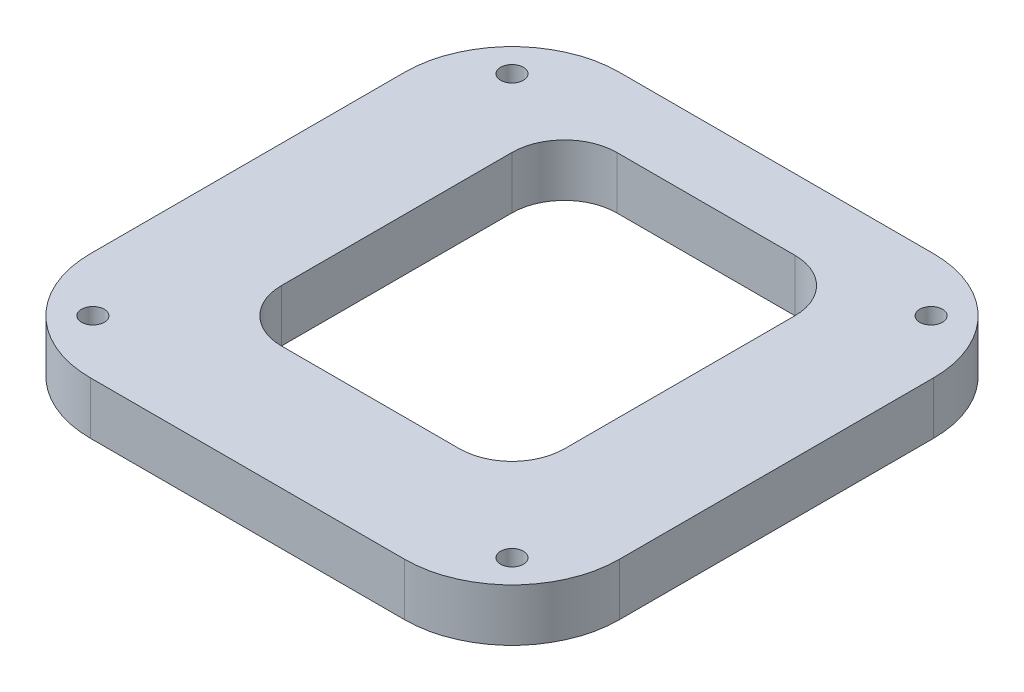
SolidWorks part; units mm, degrees
ref_plane "前视基准面" through (0, 0, 0) normal (0, 0, 1) x (1, 0, 0)
ref_plane "上视基准面" through (0, 0, 0) normal (0, 1, 0) x (1, 0, 0)
ref_plane "右视基准面" through (0, 0, 0) normal (1, 0, 0) x (0, 0, -1)
other "Configuration Table"
sketch "草图1" plane through (0, 0, 0) normal (0, 1, 0) x (1, 0, 0)
  line L0 (0, 62.6062) -> (0, -64.1627) construction
  line L1 (50.5, -50.5) -> (-50.5, -50.5)
  line L2 (50.5, -50.5) -> (50.5, 50.5)
  line L3 (50.5, 50.5) -> (-50.5, 50.5)
  line L4 (-50.5, -50.5) -> (-50.5, 50.5)
  line L5 (50.5, -50.5) -> (-50.5, 50.5) construction
  line L6 (50.5, 50.5) -> (-50.5, -50.5) construction
  line L8 (-27, 37) -> (27, 37)
  line L9 (-27, 37) -> (-27, -27)
  line L10 (-27, -27) -> (27, -27)
  line L11 (27, 37) -> (27, -27)
  point P0 (0, 0)
  dimension "D1" = 101
  dimension "D2" = 101
  dimension "D3" = 64
  dimension "D4" = 54
  dimension "D5" = 23.5
extrude "凸台-拉伸1" add sketch "草图1" along normal blind 10
fillet "圆角1" radius 20.5 4 edges at (-50.5, 5, -50.5) (-50.5, 5, 50.5) (50.5, 5, -50.5) (50.5, 5, 50.5)
fillet "圆角2" radius 10 4 edges at (27, 5, 27) (-27, 5, 27) (27, 5, -37) (-27, 5, -37)
sketch "草图2" plane through (0, 10, 0) normal (0, 1, 0) x (1, 0, 0)
  line L1 (40, -40) -> (-40, -40) construction
  line L2 (40, -40) -> (40, 40) construction
  line L3 (40, 40) -> (-40, 40) construction
  line L4 (-40, -40) -> (-40, 40) construction
  line L5 (40, -40) -> (-40, 40) construction
  line L6 (40, 40) -> (-40, -40) construction
  circle A0 centre (-40, 40) radius 2.166
  circle A1 centre (40, 40) radius 2.166
  circle A2 centre (-40, -40) radius 2.166
  circle A3 centre (40, -40) radius 2.166
  point P0 (0, 0)
  dimension "D3" = 4.332
  dimension "D1" = 80
  dimension "D2" = 80
extrude "切除-拉伸1" cut sketch "草图2" against normal through all
